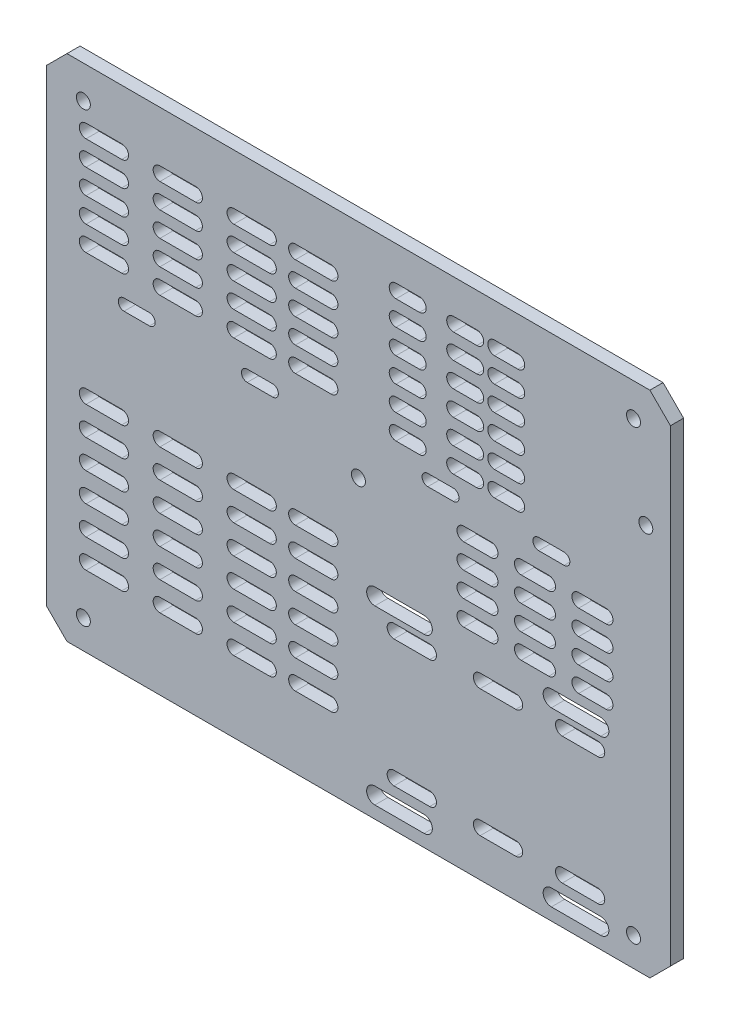
SolidWorks part; units mm, degrees
ref_plane "前视基准面" through (0, 0, 0) normal (0, 0, 1) x (1, 0, 0)
ref_plane "上视基准面" through (0, 0, 0) normal (0, 1, 0) x (1, 0, 0)
ref_plane "右视基准面" through (0, 0, 0) normal (1, 0, 0) x (0, 0, -1)
other "Configuration Table"
sketch "3.2 mounting plate - screw and strap through slots profile" plane through (0, 0, 0) normal (0, 0, 1) x (1, 0, 0)
  line L0 (-71, -62) -> (71, -62)
  line L1 (71, -62) -> (76, -57)
  line L2 (76, -57) -> (76, 57)
  line L3 (76, 57) -> (71, 62)
  line L4 (71, 62) -> (-71, 62)
  line L5 (-71, 62) -> (-76, 57)
  line L6 (-76, 57) -> (-76, -57)
  line L7 (-76, -57) -> (-71, -62)
  line L8 (-66.35, 22.35) -> (-57.65, 22.35)
  line L9 (-57.65, 25.65) -> (-66.35, 25.65)
  line L10 (-48.35, 22.35) -> (-39.65, 22.35)
  line L11 (-39.65, 25.65) -> (-48.35, 25.65)
  line L12 (-30.35, 22.35) -> (-21.65, 22.35)
  line L13 (-21.65, 25.65) -> (-30.35, 25.65)
  line L14 (-15.35, 22.35) -> (-6.65, 22.35)
  line L15 (-6.65, 25.65) -> (-15.35, 25.65)
  line L16 (-66.35, 28.35) -> (-57.65, 28.35)
  line L17 (-57.65, 31.65) -> (-66.35, 31.65)
  line L18 (-48.35, 28.35) -> (-39.65, 28.35)
  line L19 (-39.65, 31.65) -> (-48.35, 31.65)
  line L20 (-30.35, 28.35) -> (-21.65, 28.35)
  line L21 (-21.65, 31.65) -> (-30.35, 31.65)
  line L22 (-15.35, 28.35) -> (-6.65, 28.35)
  line L23 (-6.65, 31.65) -> (-15.35, 31.65)
  line L24 (-66.35, 34.35) -> (-57.65, 34.35)
  line L25 (-57.65, 37.65) -> (-66.35, 37.65)
  line L26 (-48.35, 34.35) -> (-39.65, 34.35)
  line L27 (-39.65, 37.65) -> (-48.35, 37.65)
  line L28 (-30.35, 34.35) -> (-21.65, 34.35)
  line L29 (-21.65, 37.65) -> (-30.35, 37.65)
  line L30 (-15.35, 34.35) -> (-6.65, 34.35)
  line L31 (-6.65, 37.65) -> (-15.35, 37.65)
  line L32 (-66.35, 40.35) -> (-57.65, 40.35)
  line L33 (-57.65, 43.65) -> (-66.35, 43.65)
  line L34 (-48.35, 40.35) -> (-39.65, 40.35)
  line L35 (-39.65, 43.65) -> (-48.35, 43.65)
  line L36 (-30.35, 40.35) -> (-21.65, 40.35)
  line L37 (-21.65, 43.65) -> (-30.35, 43.65)
  line L38 (-15.35, 40.35) -> (-6.65, 40.35)
  line L39 (-6.65, 43.65) -> (-15.35, 43.65)
  line L40 (-66.35, 46.35) -> (-57.65, 46.35)
  line L41 (-57.65, 49.65) -> (-66.35, 49.65)
  line L42 (-48.35, 46.35) -> (-39.65, 46.35)
  line L43 (-39.65, 49.65) -> (-48.35, 49.65)
  line L44 (-30.35, 46.35) -> (-21.65, 46.35)
  line L45 (-21.65, 49.65) -> (-30.35, 49.65)
  line L46 (-15.35, 46.35) -> (-6.65, 46.35)
  line L47 (-6.65, 49.65) -> (-15.35, 49.65)
  line L48 (-66.35, -44.65) -> (-57.65, -44.65)
  line L49 (-57.65, -41.35) -> (-66.35, -41.35)
  line L50 (-48.35, -44.65) -> (-39.65, -44.65)
  line L51 (-39.65, -41.35) -> (-48.35, -41.35)
  line L52 (-30.35, -44.65) -> (-21.65, -44.65)
  line L53 (-21.65, -41.35) -> (-30.35, -41.35)
  line L54 (-15.35, -44.65) -> (-6.65, -44.65)
  line L55 (-6.65, -41.35) -> (-15.35, -41.35)
  line L56 (-66.35, -37.65) -> (-57.65, -37.65)
  line L57 (-57.65, -34.35) -> (-66.35, -34.35)
  line L58 (-48.35, -37.65) -> (-39.65, -37.65)
  line L59 (-39.65, -34.35) -> (-48.35, -34.35)
  line L60 (-30.35, -37.65) -> (-21.65, -37.65)
  line L61 (-21.65, -34.35) -> (-30.35, -34.35)
  line L62 (-15.35, -37.65) -> (-6.65, -37.65)
  line L63 (-6.65, -34.35) -> (-15.35, -34.35)
  line L64 (-66.35, -30.65) -> (-57.65, -30.65)
  line L65 (-57.65, -27.35) -> (-66.35, -27.35)
  line L66 (-48.35, -30.65) -> (-39.65, -30.65)
  line L67 (-39.65, -27.35) -> (-48.35, -27.35)
  line L68 (-30.35, -30.65) -> (-21.65, -30.65)
  line L69 (-21.65, -27.35) -> (-30.35, -27.35)
  line L70 (-15.35, -30.65) -> (-6.65, -30.65)
  line L71 (-6.65, -27.35) -> (-15.35, -27.35)
  line L72 (-66.35, -23.65) -> (-57.65, -23.65)
  line L73 (-57.65, -20.35) -> (-66.35, -20.35)
  line L74 (-48.35, -23.65) -> (-39.65, -23.65)
  line L75 (-39.65, -20.35) -> (-48.35, -20.35)
  line L76 (-30.35, -23.65) -> (-21.65, -23.65)
  line L77 (-21.65, -20.35) -> (-30.35, -20.35)
  line L78 (-15.35, -23.65) -> (-6.65, -23.65)
  line L79 (-6.65, -20.35) -> (-15.35, -20.35)
  line L80 (-66.35, -16.65) -> (-57.65, -16.65)
  line L81 (-57.65, -13.35) -> (-66.35, -13.35)
  line L82 (-48.35, -16.65) -> (-39.65, -16.65)
  line L83 (-39.65, -13.35) -> (-48.35, -13.35)
  line L84 (-30.35, -16.65) -> (-21.65, -16.65)
  line L85 (-21.65, -13.35) -> (-30.35, -13.35)
  line L86 (-15.35, -16.65) -> (-6.65, -16.65)
  line L87 (-6.65, -13.35) -> (-15.35, -13.35)
  line L88 (-66.35, -9.65) -> (-57.65, -9.65)
  line L89 (-57.65, -6.35) -> (-66.35, -6.35)
  line L90 (-48.35, -9.65) -> (-39.65, -9.65)
  line L91 (-39.65, -6.35) -> (-48.35, -6.35)
  line L92 (-30.35, -9.65) -> (-21.65, -9.65)
  line L93 (-21.65, -6.35) -> (-30.35, -6.35)
  line L94 (-15.35, -9.65) -> (-6.65, -9.65)
  line L95 (-6.65, -6.35) -> (-15.35, -6.35)
  line L96 (9.15, 20.35) -> (14.85, 20.35)
  line L97 (14.85, 23.65) -> (9.15, 23.65)
  line L98 (23.15, 20.35) -> (28.85, 20.35)
  line L99 (28.85, 23.65) -> (23.15, 23.65)
  line L100 (33.15, 20.35) -> (38.85, 20.35)
  line L101 (38.85, 23.65) -> (33.15, 23.65)
  line L102 (9.15, 26.35) -> (14.85, 26.35)
  line L103 (14.85, 29.65) -> (9.15, 29.65)
  line L104 (23.15, 26.35) -> (28.85, 26.35)
  line L105 (28.85, 29.65) -> (23.15, 29.65)
  line L106 (33.15, 26.35) -> (38.85, 26.35)
  line L107 (38.85, 29.65) -> (33.15, 29.65)
  line L108 (9.15, 32.35) -> (14.85, 32.35)
  line L109 (14.85, 35.65) -> (9.15, 35.65)
  line L110 (23.15, 32.35) -> (28.85, 32.35)
  line L111 (28.85, 35.65) -> (23.15, 35.65)
  line L112 (33.15, 32.35) -> (38.85, 32.35)
  line L113 (38.85, 35.65) -> (33.15, 35.65)
  line L114 (9.15, 38.35) -> (14.85, 38.35)
  line L115 (14.85, 41.65) -> (9.15, 41.65)
  line L116 (23.15, 38.35) -> (28.85, 38.35)
  line L117 (28.85, 41.65) -> (23.15, 41.65)
  line L118 (33.15, 38.35) -> (38.85, 38.35)
  line L119 (38.85, 41.65) -> (33.15, 41.65)
  line L120 (9.15, 44.35) -> (14.85, 44.35)
  line L121 (14.85, 47.65) -> (9.15, 47.65)
  line L122 (23.15, 44.35) -> (28.85, 44.35)
  line L123 (28.85, 47.65) -> (23.15, 47.65)
  line L124 (33.15, 44.35) -> (38.85, 44.35)
  line L125 (38.85, 47.65) -> (33.15, 47.65)
  line L126 (9.15, 50.35) -> (14.85, 50.35)
  line L127 (14.85, 53.65) -> (9.15, 53.65)
  line L128 (23.15, 50.35) -> (28.85, 50.35)
  line L129 (28.85, 53.65) -> (23.15, 53.65)
  line L130 (33.15, 50.35) -> (38.85, 50.35)
  line L131 (38.85, 53.65) -> (33.15, 53.65)
  line L132 (25.65, -10.65) -> (32.35, -10.65)
  line L133 (32.35, -7.35) -> (25.65, -7.35)
  line L134 (39.65, -10.65) -> (46.35, -10.65)
  line L135 (46.35, -7.35) -> (39.65, -7.35)
  line L136 (53.65, -10.65) -> (60.35, -10.65)
  line L137 (60.35, -7.35) -> (53.65, -7.35)
  line L138 (25.65, -4.65) -> (32.35, -4.65)
  line L139 (32.35, -1.35) -> (25.65, -1.35)
  line L140 (39.65, -4.65) -> (46.35, -4.65)
  line L141 (46.35, -1.35) -> (39.65, -1.35)
  line L142 (53.65, -4.65) -> (60.35, -4.65)
  line L143 (60.35, -1.35) -> (53.65, -1.35)
  line L144 (25.65, 1.35) -> (32.35, 1.35)
  line L145 (32.35, 4.65) -> (25.65, 4.65)
  line L146 (39.65, 1.35) -> (46.35, 1.35)
  line L147 (46.35, 4.65) -> (39.65, 4.65)
  line L148 (53.65, 1.35) -> (60.35, 1.35)
  line L149 (60.35, 4.65) -> (53.65, 4.65)
  line L150 (25.65, 7.35) -> (32.35, 7.35)
  line L151 (32.35, 10.65) -> (25.65, 10.65)
  line L152 (39.65, 7.35) -> (46.35, 7.35)
  line L153 (46.35, 10.65) -> (39.65, 10.65)
  line L154 (53.65, 7.35) -> (60.35, 7.35)
  line L155 (60.35, 10.65) -> (53.65, 10.65)
  line L156 (4, -59) -> (16, -59)
  line L157 (16, -55) -> (4, -55)
  line L158 (47, -59) -> (59, -59)
  line L159 (59, -55) -> (47, -55)
  line L160 (4, -17) -> (16, -17)
  line L161 (16, -13) -> (4, -13)
  line L162 (47, -17) -> (59, -17)
  line L163 (59, -13) -> (47, -13)
  line L164 (8.65, -52.65) -> (17.35, -52.65)
  line L165 (17.35, -49.35) -> (8.65, -49.35)
  line L166 (29.65, -52.65) -> (38.35, -52.65)
  line L167 (38.35, -49.35) -> (29.65, -49.35)
  line L168 (49.65, -52.65) -> (58.35, -52.65)
  line L169 (58.35, -49.35) -> (49.65, -49.35)
  line L170 (8.65, -21.65) -> (17.35, -21.65)
  line L171 (17.35, -18.35) -> (8.65, -18.35)
  line L172 (29.65, -21.65) -> (38.35, -21.65)
  line L173 (38.35, -18.35) -> (29.65, -18.35)
  line L174 (49.65, -21.65) -> (58.35, -21.65)
  line L175 (58.35, -18.35) -> (49.65, -18.35)
  line L176 (-57.1, 14.6) -> (-50.9, 14.6)
  line L177 (-50.9, 17.4) -> (-57.1, 17.4)
  line L178 (-27.1, 14.6) -> (-20.9, 14.6)
  line L179 (-20.9, 17.4) -> (-27.1, 17.4)
  line L180 (16.9, 14.6) -> (23.1, 14.6)
  line L181 (23.1, 17.4) -> (16.9, 17.4)
  line L182 (43.9, 14.6) -> (50.1, 14.6)
  line L183 (50.1, 17.4) -> (43.9, 17.4)
  circle A0 centre (-67, -55) radius 1.7
  circle A1 centre (-67, 54) radius 1.7
  circle A2 centre (67, -55) radius 1.7
  circle A3 centre (67, 54) radius 1.7
  circle A4 centre (0, 8) radius 1.7
  circle A5 centre (70, 33) radius 1.7
  arc A6 (-57.65, 22.35) -> (-57.65, 25.65) centre (-57.65, 24) ccw
  arc A7 (-66.35, 25.65) -> (-66.35, 22.35) centre (-66.35, 24) ccw
  arc A8 (-39.65, 22.35) -> (-39.65, 25.65) centre (-39.65, 24) ccw
  arc A9 (-48.35, 25.65) -> (-48.35, 22.35) centre (-48.35, 24) ccw
  arc A10 (-21.65, 22.35) -> (-21.65, 25.65) centre (-21.65, 24) ccw
  arc A11 (-30.35, 25.65) -> (-30.35, 22.35) centre (-30.35, 24) ccw
  arc A12 (-6.65, 22.35) -> (-6.65, 25.65) centre (-6.65, 24) ccw
  arc A13 (-15.35, 25.65) -> (-15.35, 22.35) centre (-15.35, 24) ccw
  arc A14 (-57.65, 28.35) -> (-57.65, 31.65) centre (-57.65, 30) ccw
  arc A15 (-66.35, 31.65) -> (-66.35, 28.35) centre (-66.35, 30) ccw
  arc A16 (-39.65, 28.35) -> (-39.65, 31.65) centre (-39.65, 30) ccw
  arc A17 (-48.35, 31.65) -> (-48.35, 28.35) centre (-48.35, 30) ccw
  arc A18 (-21.65, 28.35) -> (-21.65, 31.65) centre (-21.65, 30) ccw
  arc A19 (-30.35, 31.65) -> (-30.35, 28.35) centre (-30.35, 30) ccw
  arc A20 (-6.65, 28.35) -> (-6.65, 31.65) centre (-6.65, 30) ccw
  arc A21 (-15.35, 31.65) -> (-15.35, 28.35) centre (-15.35, 30) ccw
  arc A22 (-57.65, 34.35) -> (-57.65, 37.65) centre (-57.65, 36) ccw
  arc A23 (-66.35, 37.65) -> (-66.35, 34.35) centre (-66.35, 36) ccw
  arc A24 (-39.65, 34.35) -> (-39.65, 37.65) centre (-39.65, 36) ccw
  arc A25 (-48.35, 37.65) -> (-48.35, 34.35) centre (-48.35, 36) ccw
  arc A26 (-21.65, 34.35) -> (-21.65, 37.65) centre (-21.65, 36) ccw
  arc A27 (-30.35, 37.65) -> (-30.35, 34.35) centre (-30.35, 36) ccw
  arc A28 (-6.65, 34.35) -> (-6.65, 37.65) centre (-6.65, 36) ccw
  arc A29 (-15.35, 37.65) -> (-15.35, 34.35) centre (-15.35, 36) ccw
  arc A30 (-57.65, 40.35) -> (-57.65, 43.65) centre (-57.65, 42) ccw
  arc A31 (-66.35, 43.65) -> (-66.35, 40.35) centre (-66.35, 42) ccw
  arc A32 (-39.65, 40.35) -> (-39.65, 43.65) centre (-39.65, 42) ccw
  arc A33 (-48.35, 43.65) -> (-48.35, 40.35) centre (-48.35, 42) ccw
  arc A34 (-21.65, 40.35) -> (-21.65, 43.65) centre (-21.65, 42) ccw
  arc A35 (-30.35, 43.65) -> (-30.35, 40.35) centre (-30.35, 42) ccw
  arc A36 (-6.65, 40.35) -> (-6.65, 43.65) centre (-6.65, 42) ccw
  arc A37 (-15.35, 43.65) -> (-15.35, 40.35) centre (-15.35, 42) ccw
  arc A38 (-57.65, 46.35) -> (-57.65, 49.65) centre (-57.65, 48) ccw
  arc A39 (-66.35, 49.65) -> (-66.35, 46.35) centre (-66.35, 48) ccw
  arc A40 (-39.65, 46.35) -> (-39.65, 49.65) centre (-39.65, 48) ccw
  arc A41 (-48.35, 49.65) -> (-48.35, 46.35) centre (-48.35, 48) ccw
  arc A42 (-21.65, 46.35) -> (-21.65, 49.65) centre (-21.65, 48) ccw
  arc A43 (-30.35, 49.65) -> (-30.35, 46.35) centre (-30.35, 48) ccw
  arc A44 (-6.65, 46.35) -> (-6.65, 49.65) centre (-6.65, 48) ccw
  arc A45 (-15.35, 49.65) -> (-15.35, 46.35) centre (-15.35, 48) ccw
  arc A46 (-57.65, -44.65) -> (-57.65, -41.35) centre (-57.65, -43) ccw
  arc A47 (-66.35, -41.35) -> (-66.35, -44.65) centre (-66.35, -43) ccw
  arc A48 (-39.65, -44.65) -> (-39.65, -41.35) centre (-39.65, -43) ccw
  arc A49 (-48.35, -41.35) -> (-48.35, -44.65) centre (-48.35, -43) ccw
  arc A50 (-21.65, -44.65) -> (-21.65, -41.35) centre (-21.65, -43) ccw
  arc A51 (-30.35, -41.35) -> (-30.35, -44.65) centre (-30.35, -43) ccw
  arc A52 (-6.65, -44.65) -> (-6.65, -41.35) centre (-6.65, -43) ccw
  arc A53 (-15.35, -41.35) -> (-15.35, -44.65) centre (-15.35, -43) ccw
  arc A54 (-57.65, -37.65) -> (-57.65, -34.35) centre (-57.65, -36) ccw
  arc A55 (-66.35, -34.35) -> (-66.35, -37.65) centre (-66.35, -36) ccw
  arc A56 (-39.65, -37.65) -> (-39.65, -34.35) centre (-39.65, -36) ccw
  arc A57 (-48.35, -34.35) -> (-48.35, -37.65) centre (-48.35, -36) ccw
  arc A58 (-21.65, -37.65) -> (-21.65, -34.35) centre (-21.65, -36) ccw
  arc A59 (-30.35, -34.35) -> (-30.35, -37.65) centre (-30.35, -36) ccw
  arc A60 (-6.65, -37.65) -> (-6.65, -34.35) centre (-6.65, -36) ccw
  arc A61 (-15.35, -34.35) -> (-15.35, -37.65) centre (-15.35, -36) ccw
  arc A62 (-57.65, -30.65) -> (-57.65, -27.35) centre (-57.65, -29) ccw
  arc A63 (-66.35, -27.35) -> (-66.35, -30.65) centre (-66.35, -29) ccw
  arc A64 (-39.65, -30.65) -> (-39.65, -27.35) centre (-39.65, -29) ccw
  arc A65 (-48.35, -27.35) -> (-48.35, -30.65) centre (-48.35, -29) ccw
  arc A66 (-21.65, -30.65) -> (-21.65, -27.35) centre (-21.65, -29) ccw
  arc A67 (-30.35, -27.35) -> (-30.35, -30.65) centre (-30.35, -29) ccw
  arc A68 (-6.65, -30.65) -> (-6.65, -27.35) centre (-6.65, -29) ccw
  arc A69 (-15.35, -27.35) -> (-15.35, -30.65) centre (-15.35, -29) ccw
  arc A70 (-57.65, -23.65) -> (-57.65, -20.35) centre (-57.65, -22) ccw
  arc A71 (-66.35, -20.35) -> (-66.35, -23.65) centre (-66.35, -22) ccw
  arc A72 (-39.65, -23.65) -> (-39.65, -20.35) centre (-39.65, -22) ccw
  arc A73 (-48.35, -20.35) -> (-48.35, -23.65) centre (-48.35, -22) ccw
  arc A74 (-21.65, -23.65) -> (-21.65, -20.35) centre (-21.65, -22) ccw
  arc A75 (-30.35, -20.35) -> (-30.35, -23.65) centre (-30.35, -22) ccw
  arc A76 (-6.65, -23.65) -> (-6.65, -20.35) centre (-6.65, -22) ccw
  arc A77 (-15.35, -20.35) -> (-15.35, -23.65) centre (-15.35, -22) ccw
  arc A78 (-57.65, -16.65) -> (-57.65, -13.35) centre (-57.65, -15) ccw
  arc A79 (-66.35, -13.35) -> (-66.35, -16.65) centre (-66.35, -15) ccw
  arc A80 (-39.65, -16.65) -> (-39.65, -13.35) centre (-39.65, -15) ccw
  arc A81 (-48.35, -13.35) -> (-48.35, -16.65) centre (-48.35, -15) ccw
  arc A82 (-21.65, -16.65) -> (-21.65, -13.35) centre (-21.65, -15) ccw
  arc A83 (-30.35, -13.35) -> (-30.35, -16.65) centre (-30.35, -15) ccw
  arc A84 (-6.65, -16.65) -> (-6.65, -13.35) centre (-6.65, -15) ccw
  arc A85 (-15.35, -13.35) -> (-15.35, -16.65) centre (-15.35, -15) ccw
  arc A86 (-57.65, -9.65) -> (-57.65, -6.35) centre (-57.65, -8) ccw
  arc A87 (-66.35, -6.35) -> (-66.35, -9.65) centre (-66.35, -8) ccw
  arc A88 (-39.65, -9.65) -> (-39.65, -6.35) centre (-39.65, -8) ccw
  arc A89 (-48.35, -6.35) -> (-48.35, -9.65) centre (-48.35, -8) ccw
  arc A90 (-21.65, -9.65) -> (-21.65, -6.35) centre (-21.65, -8) ccw
  arc A91 (-30.35, -6.35) -> (-30.35, -9.65) centre (-30.35, -8) ccw
  arc A92 (-6.65, -9.65) -> (-6.65, -6.35) centre (-6.65, -8) ccw
  arc A93 (-15.35, -6.35) -> (-15.35, -9.65) centre (-15.35, -8) ccw
  arc A94 (14.85, 20.35) -> (14.85, 23.65) centre (14.85, 22) ccw
  arc A95 (9.15, 23.65) -> (9.15, 20.35) centre (9.15, 22) ccw
  arc A96 (28.85, 20.35) -> (28.85, 23.65) centre (28.85, 22) ccw
  arc A97 (23.15, 23.65) -> (23.15, 20.35) centre (23.15, 22) ccw
  arc A98 (38.85, 20.35) -> (38.85, 23.65) centre (38.85, 22) ccw
  arc A99 (33.15, 23.65) -> (33.15, 20.35) centre (33.15, 22) ccw
  arc A100 (14.85, 26.35) -> (14.85, 29.65) centre (14.85, 28) ccw
  arc A101 (9.15, 29.65) -> (9.15, 26.35) centre (9.15, 28) ccw
  arc A102 (28.85, 26.35) -> (28.85, 29.65) centre (28.85, 28) ccw
  arc A103 (23.15, 29.65) -> (23.15, 26.35) centre (23.15, 28) ccw
  arc A104 (38.85, 26.35) -> (38.85, 29.65) centre (38.85, 28) ccw
  arc A105 (33.15, 29.65) -> (33.15, 26.35) centre (33.15, 28) ccw
  arc A106 (14.85, 32.35) -> (14.85, 35.65) centre (14.85, 34) ccw
  arc A107 (9.15, 35.65) -> (9.15, 32.35) centre (9.15, 34) ccw
  arc A108 (28.85, 32.35) -> (28.85, 35.65) centre (28.85, 34) ccw
  arc A109 (23.15, 35.65) -> (23.15, 32.35) centre (23.15, 34) ccw
  arc A110 (38.85, 32.35) -> (38.85, 35.65) centre (38.85, 34) ccw
  arc A111 (33.15, 35.65) -> (33.15, 32.35) centre (33.15, 34) ccw
  arc A112 (14.85, 38.35) -> (14.85, 41.65) centre (14.85, 40) ccw
  arc A113 (9.15, 41.65) -> (9.15, 38.35) centre (9.15, 40) ccw
  arc A114 (28.85, 38.35) -> (28.85, 41.65) centre (28.85, 40) ccw
  arc A115 (23.15, 41.65) -> (23.15, 38.35) centre (23.15, 40) ccw
  arc A116 (38.85, 38.35) -> (38.85, 41.65) centre (38.85, 40) ccw
  arc A117 (33.15, 41.65) -> (33.15, 38.35) centre (33.15, 40) ccw
  arc A118 (14.85, 44.35) -> (14.85, 47.65) centre (14.85, 46) ccw
  arc A119 (9.15, 47.65) -> (9.15, 44.35) centre (9.15, 46) ccw
  arc A120 (28.85, 44.35) -> (28.85, 47.65) centre (28.85, 46) ccw
  arc A121 (23.15, 47.65) -> (23.15, 44.35) centre (23.15, 46) ccw
  arc A122 (38.85, 44.35) -> (38.85, 47.65) centre (38.85, 46) ccw
  arc A123 (33.15, 47.65) -> (33.15, 44.35) centre (33.15, 46) ccw
  arc A124 (14.85, 50.35) -> (14.85, 53.65) centre (14.85, 52) ccw
  arc A125 (9.15, 53.65) -> (9.15, 50.35) centre (9.15, 52) ccw
  arc A126 (28.85, 50.35) -> (28.85, 53.65) centre (28.85, 52) ccw
  arc A127 (23.15, 53.65) -> (23.15, 50.35) centre (23.15, 52) ccw
  arc A128 (38.85, 50.35) -> (38.85, 53.65) centre (38.85, 52) ccw
  arc A129 (33.15, 53.65) -> (33.15, 50.35) centre (33.15, 52) ccw
  arc A130 (32.35, -10.65) -> (32.35, -7.35) centre (32.35, -9) ccw
  arc A131 (25.65, -7.35) -> (25.65, -10.65) centre (25.65, -9) ccw
  arc A132 (46.35, -10.65) -> (46.35, -7.35) centre (46.35, -9) ccw
  arc A133 (39.65, -7.35) -> (39.65, -10.65) centre (39.65, -9) ccw
  arc A134 (60.35, -10.65) -> (60.35, -7.35) centre (60.35, -9) ccw
  arc A135 (53.65, -7.35) -> (53.65, -10.65) centre (53.65, -9) ccw
  arc A136 (32.35, -4.65) -> (32.35, -1.35) centre (32.35, -3) ccw
  arc A137 (25.65, -1.35) -> (25.65, -4.65) centre (25.65, -3) ccw
  arc A138 (46.35, -4.65) -> (46.35, -1.35) centre (46.35, -3) ccw
  arc A139 (39.65, -1.35) -> (39.65, -4.65) centre (39.65, -3) ccw
  arc A140 (60.35, -4.65) -> (60.35, -1.35) centre (60.35, -3) ccw
  arc A141 (53.65, -1.35) -> (53.65, -4.65) centre (53.65, -3) ccw
  arc A142 (32.35, 1.35) -> (32.35, 4.65) centre (32.35, 3) ccw
  arc A143 (25.65, 4.65) -> (25.65, 1.35) centre (25.65, 3) ccw
  arc A144 (46.35, 1.35) -> (46.35, 4.65) centre (46.35, 3) ccw
  arc A145 (39.65, 4.65) -> (39.65, 1.35) centre (39.65, 3) ccw
  arc A146 (60.35, 1.35) -> (60.35, 4.65) centre (60.35, 3) ccw
  arc A147 (53.65, 4.65) -> (53.65, 1.35) centre (53.65, 3) ccw
  arc A148 (32.35, 7.35) -> (32.35, 10.65) centre (32.35, 9) ccw
  arc A149 (25.65, 10.65) -> (25.65, 7.35) centre (25.65, 9) ccw
  arc A150 (46.35, 7.35) -> (46.35, 10.65) centre (46.35, 9) ccw
  arc A151 (39.65, 10.65) -> (39.65, 7.35) centre (39.65, 9) ccw
  arc A152 (60.35, 7.35) -> (60.35, 10.65) centre (60.35, 9) ccw
  arc A153 (53.65, 10.65) -> (53.65, 7.35) centre (53.65, 9) ccw
  arc A154 (16, -59) -> (16, -55) centre (16, -57) ccw
  arc A155 (4, -55) -> (4, -59) centre (4, -57) ccw
  arc A156 (59, -59) -> (59, -55) centre (59, -57) ccw
  arc A157 (47, -55) -> (47, -59) centre (47, -57) ccw
  arc A158 (16, -17) -> (16, -13) centre (16, -15) ccw
  arc A159 (4, -13) -> (4, -17) centre (4, -15) ccw
  arc A160 (59, -17) -> (59, -13) centre (59, -15) ccw
  arc A161 (47, -13) -> (47, -17) centre (47, -15) ccw
  arc A162 (17.35, -52.65) -> (17.35, -49.35) centre (17.35, -51) ccw
  arc A163 (8.65, -49.35) -> (8.65, -52.65) centre (8.65, -51) ccw
  arc A164 (38.35, -52.65) -> (38.35, -49.35) centre (38.35, -51) ccw
  arc A165 (29.65, -49.35) -> (29.65, -52.65) centre (29.65, -51) ccw
  arc A166 (58.35, -52.65) -> (58.35, -49.35) centre (58.35, -51) ccw
  arc A167 (49.65, -49.35) -> (49.65, -52.65) centre (49.65, -51) ccw
  arc A168 (17.35, -21.65) -> (17.35, -18.35) centre (17.35, -20) ccw
  arc A169 (8.65, -18.35) -> (8.65, -21.65) centre (8.65, -20) ccw
  arc A170 (38.35, -21.65) -> (38.35, -18.35) centre (38.35, -20) ccw
  arc A171 (29.65, -18.35) -> (29.65, -21.65) centre (29.65, -20) ccw
  arc A172 (58.35, -21.65) -> (58.35, -18.35) centre (58.35, -20) ccw
  arc A173 (49.65, -18.35) -> (49.65, -21.65) centre (49.65, -20) ccw
  arc A174 (-50.9, 14.6) -> (-50.9, 17.4) centre (-50.9, 16) ccw
  arc A175 (-57.1, 17.4) -> (-57.1, 14.6) centre (-57.1, 16) ccw
  arc A176 (-20.9, 14.6) -> (-20.9, 17.4) centre (-20.9, 16) ccw
  arc A177 (-27.1, 17.4) -> (-27.1, 14.6) centre (-27.1, 16) ccw
  arc A178 (23.1, 14.6) -> (23.1, 17.4) centre (23.1, 16) ccw
  arc A179 (16.9, 17.4) -> (16.9, 14.6) centre (16.9, 16) ccw
  arc A180 (50.1, 14.6) -> (50.1, 17.4) centre (50.1, 16) ccw
  arc A181 (43.9, 17.4) -> (43.9, 14.6) centre (43.9, 16) ccw
extrude "3.2 mounting plate - screw and strap through slots" add sketch "3.2 mounting plate - screw and strap through slots profile" along normal blind 3.2
